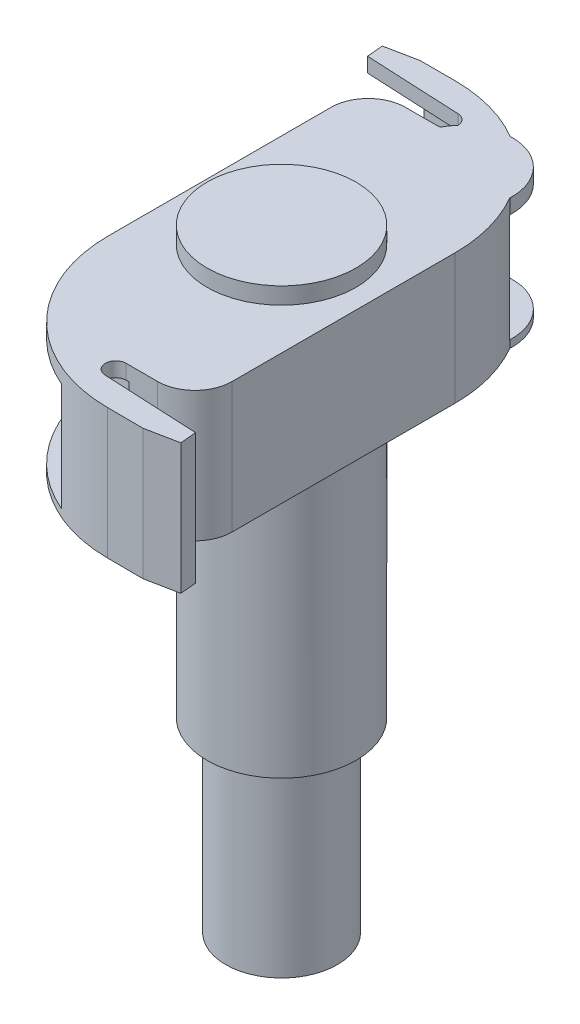
SolidWorks part; units mm, degrees
ref_plane "Front Plane" through (0, 0, 0) normal (0, 0, 1) x (1, 0, 0)
ref_plane "Top Plane" through (0, 0, 0) normal (0, 1, 0) x (1, 0, 0)
ref_plane "Right Plane" through (0, 0, 0) normal (1, 0, 0) x (0, 0, -1)
sketch "Sketch1" plane through (0, 0, 0) normal (0, 1, 0) x (1, 0, 0)
  circle A0 centre (0, 0) radius 1.5
  dimension "D1" = 3
extrude "Boss-Extrude1" add sketch "Sketch1" along normal blind 5
sketch "Sketch2" plane through (0, 5, 0) normal (0, 1, 0) x (1, 0, 0)
  circle A0 centre (0, 0) radius 2
  dimension "D1" = 4
extrude "Boss-Extrude2" add sketch "Sketch2" along normal blind 11.45
ref_plane "Plane1" through (0, 12.5, 0) normal (0, 1, 0) x (1, 0, 0)
sketch "Sketch3" plane through (0, 12.5, 0) normal (0, 1, 0) x (1, 0, 0)
  circle A0 centre (0, 0) radius 2.8202
  circle A1 centre (0, 0) radius 9
  circle A2 centre (0, 0) radius 10
  dimension "D1" = 18
  dimension "D2" = 1
sketch "Sketch6" plane through (0, 12.5, 0) normal (0, 1, 0) x (1, 0, 0)
  line L0 (-2.524, -2.1301) -> (-2.524, 3.8513)
  line L4 (-2.524, -6.1058) -> (1.7694, 4.2805) construction
  line L5 (-2.524, 5.4079) -> (2.524, -5.4079) construction
  line L6 (-3.8005, 4.8513) -> (-1.318, 4.8513) construction
  line L9 (-1.476, 6.1359) -> (-2.4122, 6.1359)
  line L11 (-3.2223, 5.5319) -> (-0.6644, 5.4078)
  line L13 (-2.4122, 6.1359) -> (-3.2619, 5.9665)
  line L14 (-3.2223, 5.5319) -> (-3.2619, 5.9665)
  line L16 (-1.524, 4.8513) -> (-0.668, 4.8513)
  line L18 (0, 0) -> (3.8308, 0) construction
  line L19 (0, 0) -> (0, 3.0738) construction
  line L20 (3.8005, 4.8513) -> (1.318, 4.8513) construction
  line L21 (2.524, -3.8513) -> (2.524, 2.1359)
  line L26 (1.4516, -6.1301) -> (2.4122, -6.1359)
  line L27 (2.4122, -6.1359) -> (3.2619, -5.9665)
  line L28 (3.2223, -5.5319) -> (3.2619, -5.9665)
  line L29 (3.2223, -5.5319) -> (0.6644, -5.4078)
  line L30 (1.524, -4.8513) -> (0.668, -4.8513)
  arc A0 (-0.6644, 5.4078) -> (-0.668, 4.8513) centre (-0.6779, 5.1296) cw
  arc A1 (-2.524, 3.8513) -> (-1.524, 4.8513) centre (-1.524, 3.8513) cw
  arc A3 (-2.524, -2.1301) -> (1.4516, -6.1301) centre (1.476, -2.1301) ccw
  arc A4 (0.6644, -5.4078) -> (0.668, -4.8513) centre (0.6779, -5.1296) cw
  arc A5 (2.524, -3.8513) -> (1.524, -4.8513) centre (1.524, -3.8513) cw
  arc A6 (-1.476, 6.1359) -> (2.524, 2.1359) centre (-1.476, 2.1359) cw
  point P1 (0, 0)
  point P15 (-1.5249, 4.9)
  point P24 (-2.524, 4.8513)
  point P41 (2.524, 4.8513)
  point P42 (1.5249, 4.9)
  point P46 (2.837, -6.0512)
  dimension "D1" = 1
  dimension "D2" = 4
extrude "Boss-Extrude6" add sketch "Sketch6" along normal blind 3.5
sketch "Sketch4" plane through (0, 12.5, 0) normal (0, 1, 0) x (1, 0, 0)
  line L1 (0.8824, -3.9596) -> (1.9717, 4.025)
  line L2 (-1.8354, -3.5888) -> (-0.7461, 4.3957)
  line L4 (0.7461, -4.3957) -> (-0.7461, 4.3957) construction
  line L5 (-1.2908, 0.4035) -> (-2.9377, 0.6282) construction
  arc A0 (-1.8354, -3.5888) -> (0.8824, -3.9596) centre (-0.4765, -3.7742) ccw
  arc A1 (-0.7461, 4.3957) -> (1.9717, 4.025) centre (0.6128, 4.2103) cw
  circle A3 centre (-0.4765, -3.7742) radius 0.5
  circle A4 centre (0.6128, 4.2103) radius 0.5
  point P0 (0, 0)
  dimension "D1" = 1
  dimension "D2" = 1
extrude "Boss-Extrude5" add sketch "Sketch4" along normal blind 3.5
sketch "Sketch5" plane through (1.3966, 0, 0.1905) normal (0.9908, 0, 0.1352) x (0.1352, 0, -0.9908)
  line L0 (0, 16.45) -> (0, 12.5842) construction
  line L1 (2, 16.45) -> (-2, 16.45) construction
  line L2 (-5.7671, 12.7018) -> (-2.7527, 12.7018)
  line L3 (5.7671, 15.6069) -> (2.7527, 15.6069)
  line L4 (5.7671, 15.6069) -> (5.7671, 12.7018)
  line L5 (5.7671, 12.7018) -> (2.7527, 12.7018)
  line L6 (2.7527, 15.6069) -> (2.7527, 12.7018)
  line L7 (-2.7527, 15.6069) -> (-2.7527, 12.7018)
  line L8 (-5.7671, 15.6069) -> (-2.7527, 15.6069)
  line L9 (-5.7671, 15.6069) -> (-5.7671, 12.7018)
extrude "Cut-Extrude1" cut sketch "Sketch5" against normal through all
